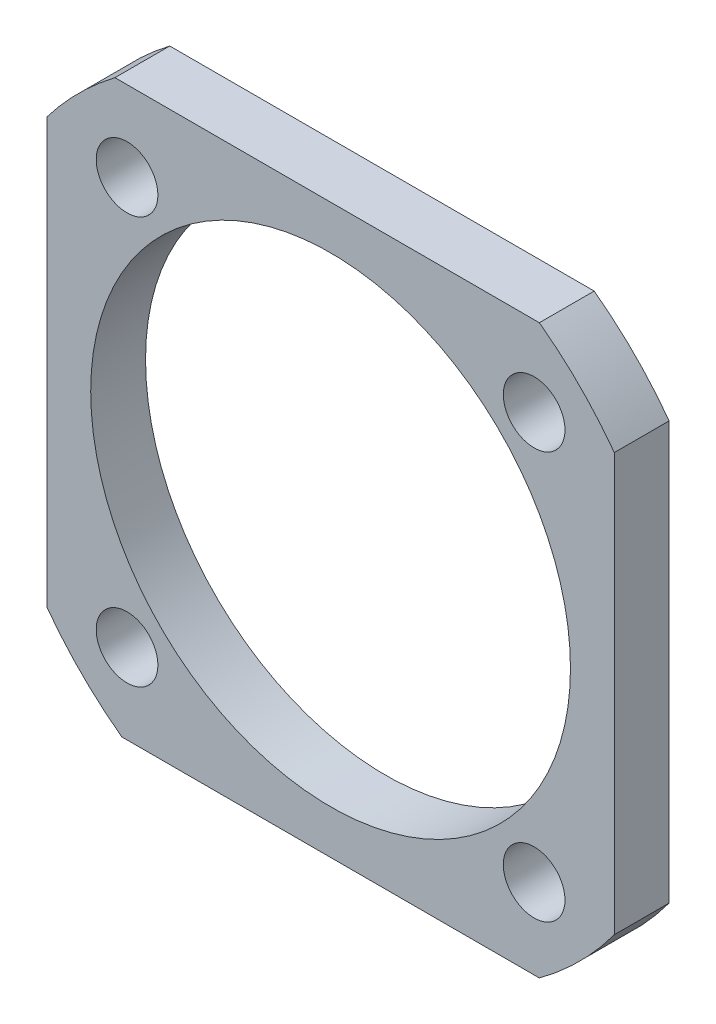
SolidWorks part; units mm, degrees
ref_plane "Front Plane" through (0, 0, 0) normal (0, 0, 1) x (1, 0, 0)
ref_plane "Top Plane" through (0, 0, 0) normal (0, 1, 0) x (1, 0, 0)
ref_plane "Right Plane" through (0, 0, 0) normal (1, 0, 0) x (0, 0, -1)
sketch "Sketch1" plane through (0, 0, 0) normal (0, 0, 1) x (1, 0, 0)
  line L4 (-20.7, 15.7325) -> (-20.7, -15.2315)
  line L5 (-15.2315, -20.7) -> (15.2315, -20.7)
  line L6 (20.7, -15.2315) -> (20.7, 15.2315)
  line L7 (15.2315, 20.7) -> (-15.7325, 20.7)
  line L8 (-20.7, 15.7325) -> (-20.7, -15.2315)
  line L9 (-15.2315, -20.7) -> (15.2315, -20.7)
  line L10 (20.7, -15.2315) -> (20.7, 15.2315)
  line L11 (15.2315, 20.7) -> (-15.7325, 20.7)
  circle A0 centre (-14.8492, -14.8492) radius 2.25 construction
  circle A1 centre (-14.8492, 14.8492) radius 2.25 construction
  circle A2 centre (14.8492, 14.8492) radius 2.25 construction
  circle A3 centre (14.8492, -14.8492) radius 2.25 construction
  arc A4 (-20.7, -15.2315) -> (-15.2315, -20.7) centre (0, 0) ccw
  arc A5 (15.2315, -20.7) -> (20.7, -15.2315) centre (0, 0) ccw
  arc A6 (20.7, 15.2315) -> (15.2315, 20.7) centre (0, 0) ccw
  arc A7 (-15.7325, 20.7) -> (-20.7, 15.7325) centre (0, 0) ccw
  arc A8 (-20.7, -15.2315) -> (-15.2315, -20.7) centre (0, 0) ccw
  arc A9 (15.2315, -20.7) -> (20.7, -15.2315) centre (0, 0) ccw
  arc A10 (20.7, 15.2315) -> (15.2315, 20.7) centre (0, 0) ccw
  arc A11 (-15.7325, 20.7) -> (-20.7, 15.7325) centre (0, 0) ccw
  circle A12 centre (-14.8492, -14.8492) radius 2.25
  circle A13 centre (-14.8492, 14.8492) radius 2.25
  circle A14 centre (14.8492, 14.8492) radius 2.25
  circle A15 centre (14.8492, -14.8492) radius 2.25
  circle A18 centre (0, 0) radius 17.5 construction
  circle A19 centre (0, 0) radius 17.5
  dimension "D1" = 0
extrude "Boss-Extrude1" add sketch "Sketch1" along normal blind 4
